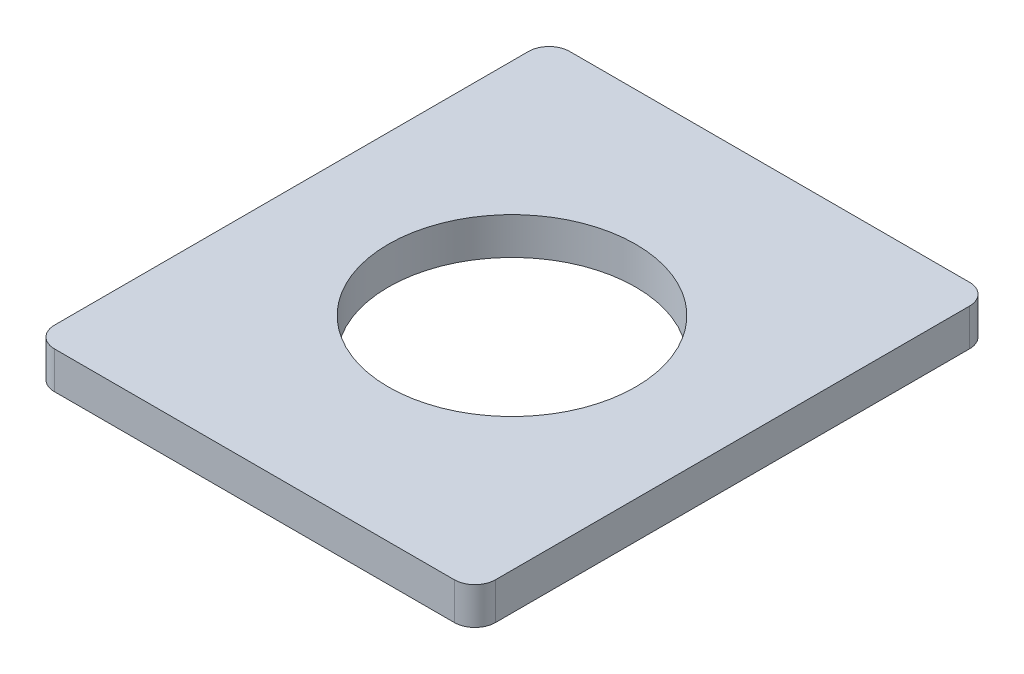
SolidWorks part; units mm, degrees
ref_plane "前视基准面" through (0, 0, 0) normal (0, 0, 1) x (1, 0, 0)
ref_plane "上视基准面" through (0, 0, 0) normal (0, 1, 0) x (1, 0, 0)
ref_plane "右视基准面" through (0, 0, 0) normal (1, 0, 0) x (0, 0, -1)
other "Configuration Table"
sketch "草图1" plane through (0, 0, 0) normal (0, 1, 0) x (1, 0, 0)
  line L1 (-107, -125) -> (107, -125)
  line L2 (-107, -125) -> (-107, 125)
  line L3 (-107, 125) -> (107, 125)
  line L4 (107, -125) -> (107, 125)
  circle A0 centre (0, 0) radius 60
  point P4 (-107, 0)
  point P6 (0, 125)
  point P9 (0, 0)
  dimension "D3" = 120
  dimension "D1" = 250
  dimension "D2" = 214
extrude "凸台-拉伸1" add sketch "草图1" along normal blind 18
fillet "圆角1" radius 10 4 edges at (-107, 9, -125) (107, 9, -125) (107, 9, 125) (-107, 9, 125)
